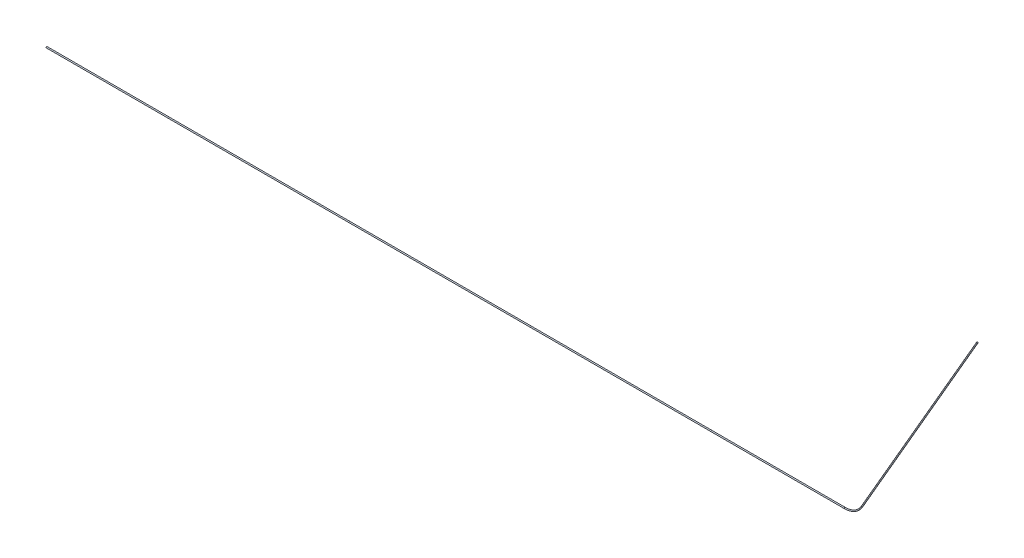
SolidWorks part; units mm, degrees
ref_plane "Front Plane" through (0, 0, 0) normal (0, 0, 1) x (1, 0, 0)
ref_plane "Top Plane" through (0, 0, 0) normal (0, 1, 0) x (1, 0, 0)
ref_plane "Right Plane" through (0, 0, 0) normal (1, 0, 0) x (0, 0, -1)
sketch "Sketch1" plane through (0, 0, 0) normal (1, 0, 0) x (0, 0, -1)
  circle A0 centre (0, 0) radius 0.875
  dimension "D1" = 1.75
sketch "Sketch2" plane through (0, 0, 0) normal (0, 0, 1) x (1, 0, 0)
  line L0 (0, 0) -> (1219.2, 0)
  line L1 (1245.1808, 15) -> (1421.1571, 319.8)
  arc A0 (1219.2, 0) -> (1245.1808, 15) centre (1219.2, 30) ccw
  dimension "D2" = 30
  dimension "D1" = 120
  dimension "D4" = 1219.2
  dimension "D5" = 304.8
sweep "Sweep1" add profiles "Sketch1" path "Sketch2"
